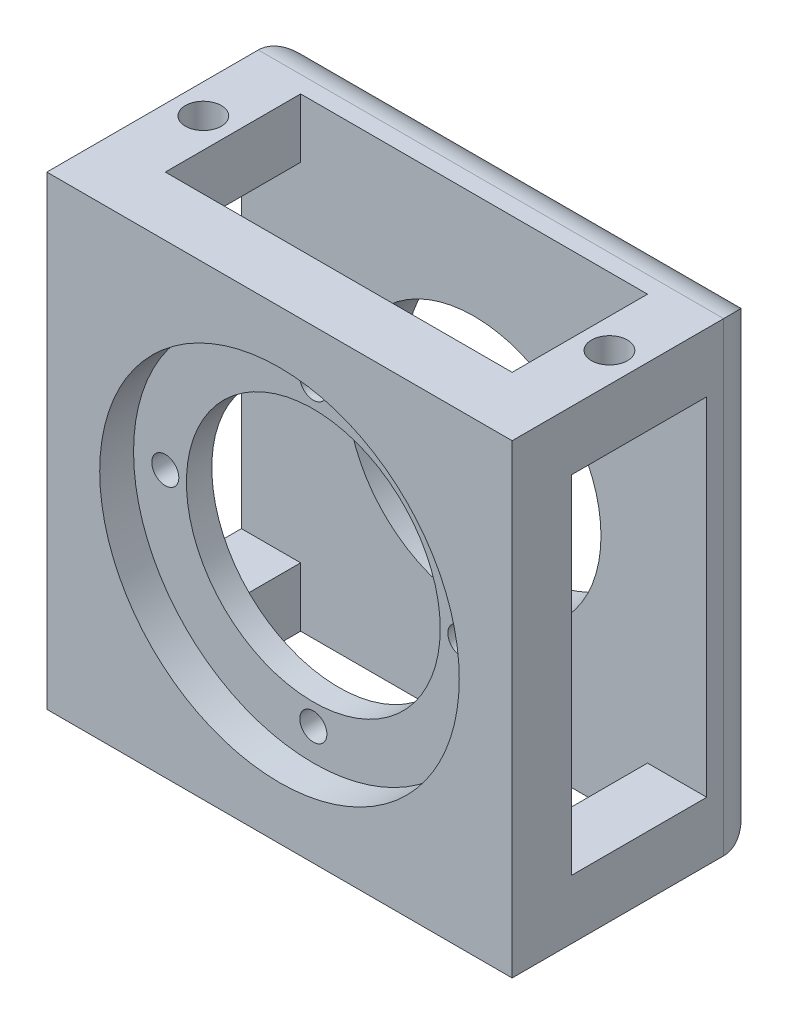
SolidWorks part; units mm, degrees
ref_plane "Front Plane" through (0, 0, 0) normal (0, 0, 1) x (1, 0, 0)
ref_plane "Top Plane" through (0, 0, 0) normal (0, 1, 0) x (1, 0, 0)
ref_plane "Right Plane" through (0, 0, 0) normal (1, 0, 0) x (0, 0, -1)
sketch "Sketch1" plane through (0, 0, 0) normal (0, 0, 1) x (1, 0, 0)
  line L1 (-27.5, 27.5) -> (27.5, 27.5)
  line L2 (-27.5, 27.5) -> (-27.5, -27.5)
  line L3 (-27.5, -27.5) -> (27.5, -27.5)
  line L4 (27.5, 27.5) -> (27.5, -27.5)
  dimension "D1" = 55
  dimension "D2" = 55
  dimension "D3" = 27.5
  dimension "D4" = 27.5
extrude "Boss-Extrude1" add sketch "Sketch1" along normal blind 30
sketch "Sketch4" plane through (0, 27.5, 0) normal (0, 1, 0) x (1, 0, 0)
  line L0 (-27.5, -30) -> (-27.5, 0) construction
  line L1 (-20.5, -7) -> (20.5, -7)
  line L2 (-20.5, -7) -> (-20.5, -23)
  line L3 (-20.5, -23) -> (20.5, -23)
  line L4 (20.5, -7) -> (20.5, -23)
  line L5 (27.5, 0) -> (-27.5, 0) construction
  dimension "D1" = 41
  dimension "D2" = 7
  dimension "D3" = 16
  dimension "7" = 7
extrude "Cut-Extrude1" cut sketch "Sketch4" against normal through all
sketch "Sketch5" plane through (27.5, 0, 0) normal (1, 0, 0) x (0, 0, -1)
  line L0 (-30, 27.5) -> (0, 27.5) construction
  line L1 (-23, 20.5) -> (-7, 20.5)
  line L2 (-23, 20.5) -> (-23, -20.5)
  line L3 (-23, -20.5) -> (-7, -20.5)
  line L4 (-7, 20.5) -> (-7, -20.5)
  line L5 (0, -27.5) -> (0, 27.5) construction
  dimension "D1" = 41
  dimension "D2" = 7
  dimension "D3" = 16
  dimension "D4" = 7
extrude "Cut-Extrude2" cut sketch "Sketch5" against normal blind 60
sketch "Sketch7" plane through (0, 0, 30) normal (0, 0, 1) x (1, 0, 0)
  circle A0 centre (0, 0) radius 21.25
  dimension "D1" = 42.5
extrude "Cut-Extrude3" cut sketch "Sketch7" against normal blind 4
sketch "Sketch8" plane through (0, 0, 26) normal (0, 0, 1) x (1, 0, 0)
  circle A0 centre (0, 0) radius 15
  dimension "D1" = 30
extrude "Cut-Extrude4" cut sketch "Sketch8" against normal blind 50
sketch "Sketch9" plane through (0, 0, 26) normal (0, 0, 1) x (1, 0, 0)
  circle A0 centre (0, 17.5) radius 1.6
  circle A1 centre (17.5, 0) radius 1.6
  circle A2 centre (0, -17.5) radius 1.6
  circle A3 centre (-17.5, 0) radius 1.6
  point P12 (0, 0)
  dimension "D1" = 3.2
  dimension "D2" = 17.5
  dimension "D3" = 4
extrude "Cut-Extrude5" cut sketch "Sketch9" against normal blind 10
sketch "Sketch11" plane through (0, 27.5, 0) normal (0, 1, 0) x (1, 0, 0)
  line L1 (-27.5, -30) -> (-27.5, 0) construction
  line L2 (27.5, -30) -> (27.5, 0) construction
  line L3 (20.5, -7) -> (-20.5, -7) construction
  circle A0 centre (-24, -15) radius 2.125
  circle A1 centre (24, -15) radius 2.125
  dimension "D1" = 4.25
  dimension "D2" = 4.25
  dimension "D3" = 3.5
  dimension "D4" = 3.5
  dimension "D5" = 8
extrude "Cut-Extrude6" cut sketch "Sketch11" against normal blind 10
fillet "Fillet2" radius 5 4 edges at (0, -27.5, 0) (0, 27.5, 0) (27.5, 0, 0) (-27.5, 0, 0)
